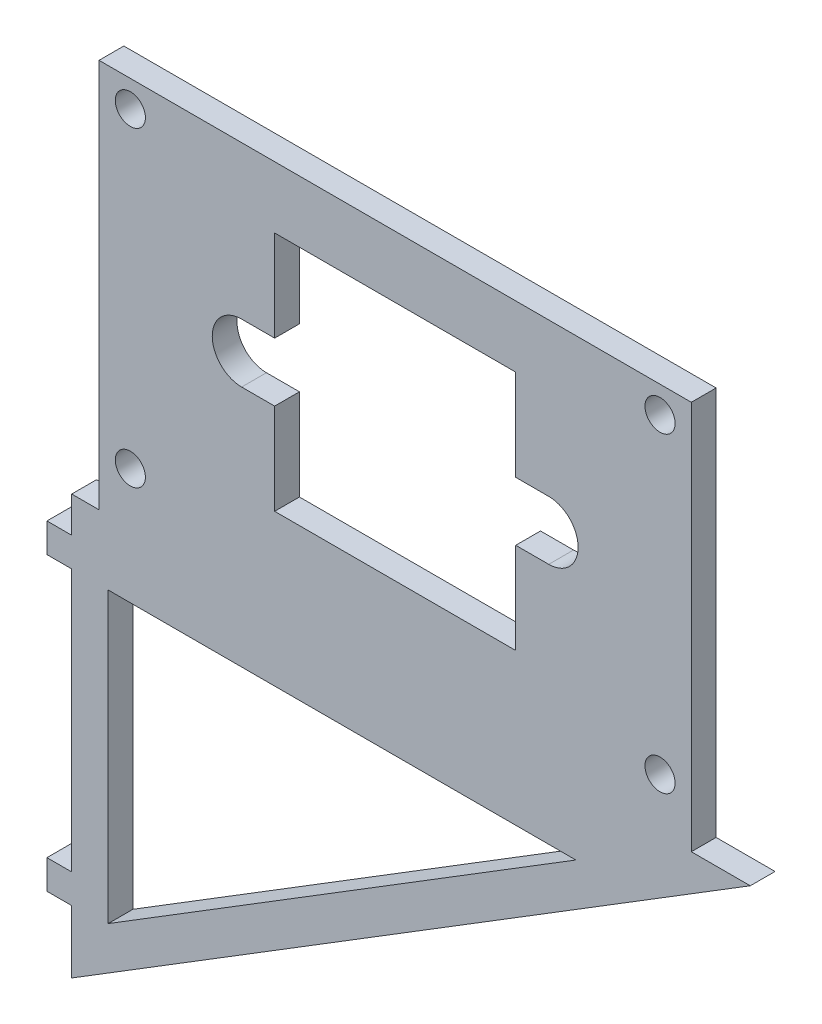
SolidWorks part; units mm, degrees
material "Delrin 2700 NC010, Low Viscosity Acetal Copolymer (SS)"
ref_plane "Front Plane" through (0, 0, 0) normal (0, 0, 1) x (1, 0, 0)
ref_plane "Top Plane" through (0, 0, 0) normal (0, 1, 0) x (1, 0, 0)
ref_plane "Right Plane" through (0, 0, 0) normal (1, 0, 0) x (0, 0, -1)
sketch "Sketch1" plane through (0, 0, 0) normal (0, 0, 1) x (1, 0, 0)
  line L0 (0, 0) -> (47.2887, 29.21)
  line L1 (2.54, 24.6888) -> (35.136, 24.6888)
  line L2 (2.54, 4.5544) -> (2.54, 24.6888)
  line L4 (0, 0) -> (0, 4.3688)
  line L5 (2.54, 6.4008) -> (2.54, 24.6888) construction
  line L6 (2.54, 4.5544) -> (35.136, 24.6888)
  line L44 (22.5425, 14.605) -> (22.5425, 24.13) construction
  line L45 (14.1425, 41.5872) -> (14.1425, 35.2372)
  line L46 (1.905, 29.21) -> (1.905, 56.3372)
  line L47 (1.905, 56.3372) -> (43.18, 56.3372)
  line L48 (43.18, 29.21) -> (43.18, 56.3372)
  line L49 (1.905, 43.6372) -> (43.18, 43.6372) construction
  line L50 (30.9425, 52.0372) -> (14.1425, 52.0372)
  line L55 (1.905, 29.21) -> (0, 29.21)
  line L56 (0, 26.7208) -> (-1.7272, 26.7208)
  line L57 (-1.7272, 6.4008) -> (-1.7272, 4.3688)
  line L58 (0, 24.6888) -> (-1.7272, 24.6888)
  line L59 (-1.7272, 26.7208) -> (-1.7272, 24.6888)
  line L60 (30.9425, 52.0372) -> (30.9425, 45.6872)
  line L61 (30.9425, 35.2372) -> (14.1425, 35.2372)
  line L62 (14.1425, 52.0372) -> (14.1425, 45.6872)
  line L63 (30.9425, 52.0372) -> (14.1425, 35.2372) construction
  line L64 (30.9425, 35.2372) -> (14.1425, 52.0372) construction
  line L66 (14.1425, 41.5872) -> (11.8425, 41.5872)
  line L67 (30.9425, 41.5872) -> (33.2425, 41.5872)
  line L68 (14.1425, 45.6872) -> (11.8425, 45.6872)
  line L69 (30.9425, 45.6872) -> (33.2425, 45.6872)
  line L70 (0, 26.7208) -> (0, 29.21)
  line L71 (30.9425, 41.5872) -> (30.9425, 35.2372)
  line L74 (0, 4.3688) -> (-1.7272, 4.3688)
  line L75 (0, 6.4008) -> (-1.7272, 6.4008)
  line L76 (0, 6.4008) -> (0, 24.6888)
  line L108 (47.2887, 29.21) -> (43.18, 29.21)
  arc A0 (11.8425, 41.5872) -> (11.8425, 45.6872) centre (11.8425, 43.6372) cw
  arc A1 (33.2425, 41.5872) -> (33.2425, 45.6872) centre (33.2425, 43.6372) ccw
  point P56 (22.5425, 43.6372)
  point P60 (22.5425, 56.3372)
  dimension "D14" = 12.7
  dimension "D2" = 29.21
  dimension "D3" = 2.54
  dimension "D12" = 41.275
  dimension "D15" = 16.8
  dimension "D16" = 2.032
  dimension "D17" = 1.7272
  dimension "D19" = 16.8
  dimension "D20" = 4.1
  dimension "D21" = 2.3
  dimension "D25" = 1.905
  dimension "D24" = 2
extrude "Boss-Extrude1" add sketch "Sketch1" along normal blind 1.7272
fillet "Fillet7" [suppressed] radius 15.24
sketch "Sketch2"
  line L0 (0, 26.7208) -> (0, 24.6888) construction
  line L1 (0, 24.6888) -> (-1.7272, 24.6888) construction
  line L2 (-1.7272, 24.6888) -> (-1.7272, 26.7208) construction
  line L3 (-1.7272, 26.7208) -> (0, 26.7208) construction
  line L4 (0, 6.4008) -> (0, 4.3688) construction
  line L5 (0, 4.3688) -> (-1.7272, 4.3688) construction
  line L6 (-1.7272, 4.3688) -> (-1.7272, 6.4008) construction
  line L7 (-1.7272, 6.4008) -> (0, 6.4008) construction
  line L8 (0, 26.7208) -> (0, 24.6888)
  line L9 (0, 24.6888) -> (-1.7272, 24.6888)
  line L10 (-1.7272, 24.6888) -> (-1.7272, 26.7208)
  line L11 (-1.7272, 26.7208) -> (0, 26.7208)
  line L12 (0, 6.4008) -> (0, 4.3688)
  line L13 (0, 4.3688) -> (-1.7272, 4.3688)
  line L14 (-1.7272, 4.3688) -> (-1.7272, 6.4008)
  line L15 (-1.7272, 6.4008) -> (0, 6.4008)
sketch "Sketch3" plane through (22.5425, 43.6372, 1.7272) normal (0, 0, 1) x (1, 0, 0)
  circle A0 centre (-18.4568, 10.8495) radius 1.05
  circle A1 centre (-18.4568, -10.8495) radius 1.05
  circle A2 centre (18.4568, -10.8495) radius 1.05
  circle A3 centre (18.4568, 10.8495) radius 1.05
  point P0 (0, 0)
extrude "Cut-Extrude1" cut sketch "Sketch3" against normal up to surface (1.7272 mm away) up to face at (22.5425, 43.6372, 0)
